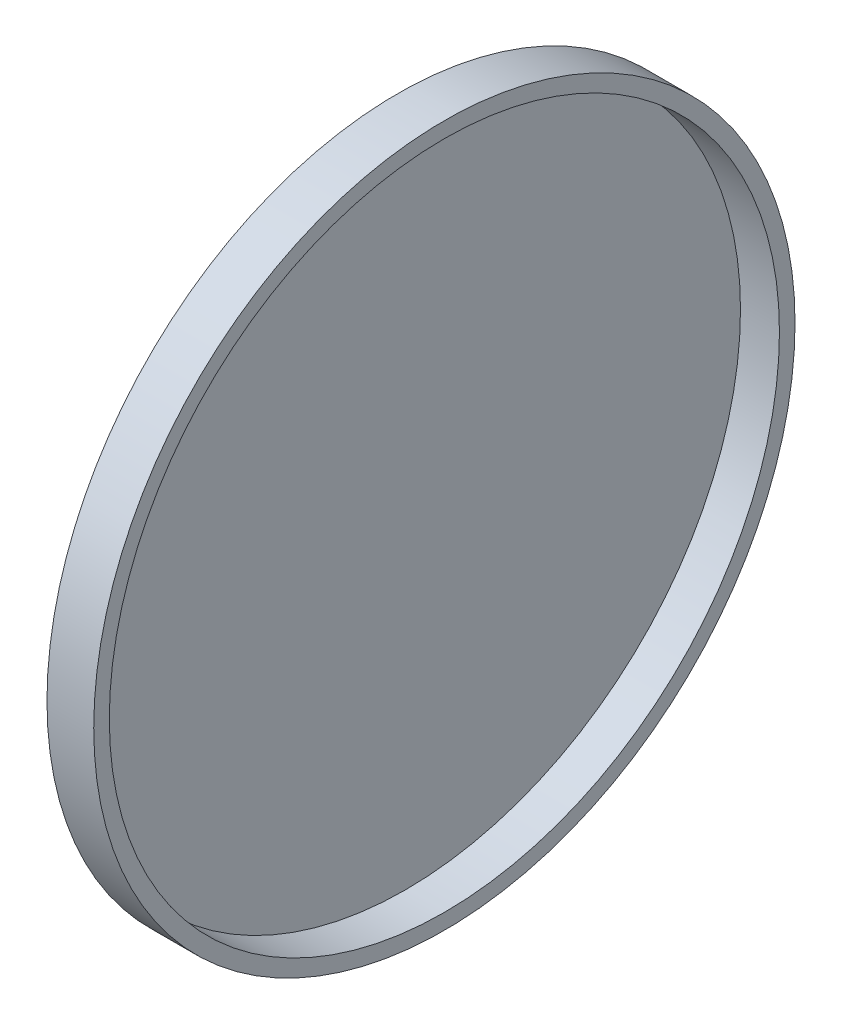
SolidWorks part; units mm, degrees
ref_plane "Front Plane" through (0, 0, 0) normal (0, 0, 1) x (1, 0, 0)
ref_plane "Top Plane" through (0, 0, 0) normal (0, 1, 0) x (1, 0, 0)
ref_plane "Right Plane" through (0, 0, 0) normal (1, 0, 0) x (0, 0, -1)
sketch "Sketch1" plane through (0, 0, 0) normal (1, 0, 0) x (0, 0, -1)
  circle A0 centre (0, 0) radius 43
  circle A1 centre (0, 0) radius 45
  dimension "D1" = 86
  dimension "D2" = 2
extrude "Boss-Extrude1" add sketch "Sketch1" along normal blind 5
sketch "Sketch2" plane through (0, 0, 0) normal (-1, 0, 0) x (0, 0, 1)
  circle A0 centre (0, 0) radius 45
extrude "Boss-Extrude2" add sketch "Sketch2" along normal blind 1
